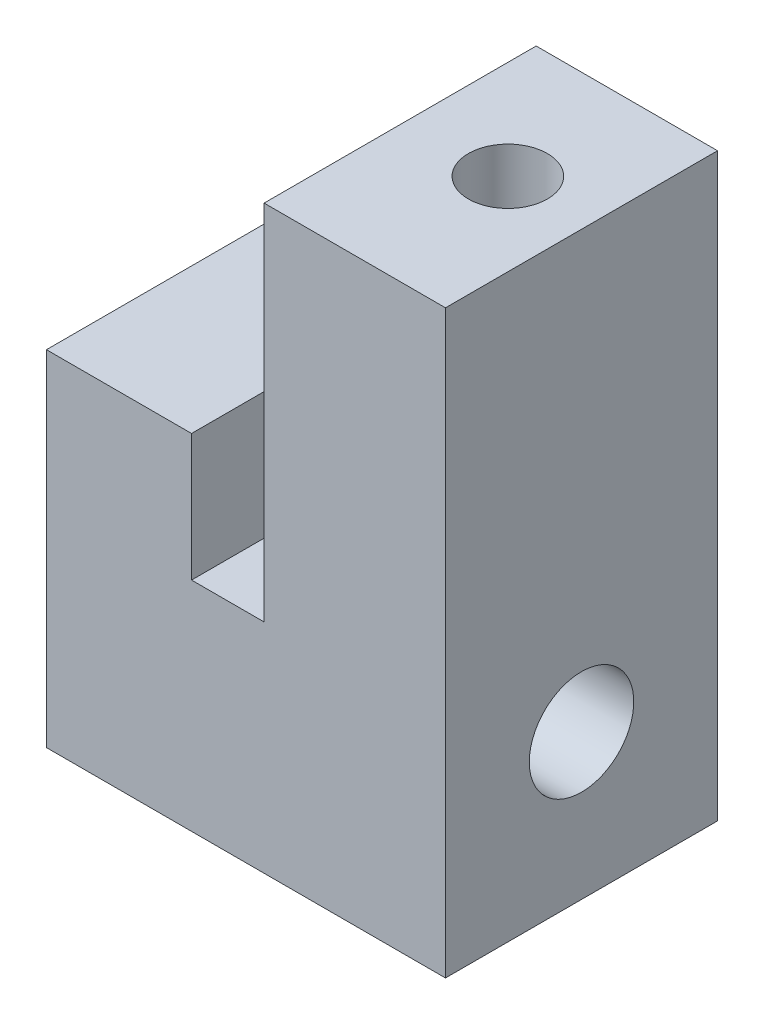
SolidWorks part; units mm, degrees
ref_plane "Front Plane" through (0, 0, 0) normal (0, 0, 1) x (1, 0, 0)
ref_plane "Top Plane" through (0, 0, 0) normal (0, 1, 0) x (1, 0, 0)
ref_plane "Right Plane" through (0, 0, 0) normal (1, 0, 0) x (0, 0, -1)
sketch "Sketch1" plane through (0, 0, 0) normal (0, 1, 0) x (1, 0, 0)
  line L1 (0, 0) -> (17.4625, 0)
  line L2 (0, 0) -> (0, 11.9062)
  line L3 (0, 11.9062) -> (17.4625, 11.9062)
  line L4 (17.4625, 0) -> (17.4625, 11.9062)
extrude "Boss-Extrude1" add sketch "Sketch1" along normal blind 25.4
sketch "Sketch2" plane through (0, 0, 0) normal (0, 0, 1) x (1, 0, 0)
  line L0 (6.35, 15.0812) -> (6.35, 9.525)
  line L5 (0, 25.4) -> (17.4625, 25.4)
  line L6 (6.35, 9.525) -> (9.525, 9.525)
  line L7 (6.35, 15.0812) -> (9.525, 15.0812)
  line L8 (0, 25.4) -> (0, 0)
  line L9 (6.35, 15.0812) -> (6.35, 9.525)
  line L10 (0, 25.4) -> (17.4625, 25.4) construction
  line L11 (0, 0) -> (17.4625, 0)
  line L12 (6.35, 9.525) -> (9.525, 9.525)
  line L13 (9.525, 15.0812) -> (9.525, 9.525)
  line L14 (9.525, 15.0812) -> (0, 15.0812)
  line L15 (9.525, 15.0812) -> (9.525, 9.525)
  line L16 (9.525, 9.525) -> (6.35, 9.525)
  line L17 (6.35, 15.0812) -> (6.35, 9.525)
  line L18 (9.525, 15.0812) -> (9.525, 25.4)
  line L19 (17.4625, 25.4) -> (17.4625, 0)
  line L20 (0, 25.4) -> (9.525, 25.4)
  line L21 (0, 25.4) -> (0, 15.0812)
  line L22 (0, 15.0812) -> (9.525, 15.0812)
  line L23 (9.525, 25.4) -> (9.525, 15.0812)
  line L25 (6.35, 9.525) -> (6.35, 0)
  line L26 (6.35, 0) -> (17.4625, 0)
  line L27 (17.4625, 9.525) -> (17.4625, 0)
  line L29 (17.4625, 9.525) -> (17.4625, 25.4)
  line L30 (17.4625, 25.4) -> (9.525, 25.4)
  line L31 (9.525, 9.525) -> (9.525, 25.4)
  line M4 (0, 25.4) -> (0, 0)
extrude "Cut-Extrude1" cut sketch "Sketch2" against normal blind 25.4 contours L7 L18 L5 L14 M4 | L13 L7 L0 L6
sketch "Sketch4" plane through (0, 0, 0) normal (-1, 0, 0) x (0, 0, 1)
  line L0 (-5.9531, 0) -> (-5.9531, 4.064)
  line L1 (-11.9062, 0) -> (0, 0) construction
  line L2 (-5.9531, 4.064) -> (-5.9531, 6.35)
  circle A0 centre (-5.9531, 6.35) radius 2.286
extrude "Cut-Extrude2" cut sketch "Sketch4" against normal blind 25.4
sketch "Sketch5" plane through (0, 25.4, 0) normal (0, 1, 0) x (1, 0, 0)
  line L0 (17.4625, 6.35) -> (15.494, 6.35)
  line L1 (17.4625, 0) -> (17.4625, 11.9062) construction
  line L2 (15.494, 6.35) -> (13.843, 6.35)
  circle A0 centre (13.843, 6.35) radius 1.651
hole_wizard "#8-32 Tapped Hole1" positions "Sketch7" profile "Sketch6" tap size "#8-32" standard "ANSI Inch"
sketch "Sketch7" plane through (0, 25.4, 0) normal (0, 1, 0) x (1, 0, 0)
  point P0 (13.843, 6.35)
sketch "Sketch6" plane through (13.843, 25.4, -6.35) normal (1, 0, 0) x (0, 0, 1)
  line L0 (0, 0) -> (0, 12.1503)
  line L1 (0, 12.1503) -> (1.7272, 11.1125)
  line L2 (1.7272, 11.1125) -> (1.7272, 0)
  line L5 (1.7272, 0) -> (0, 0)
  line L10 (0, 12.1503) -> (-1.7272, 11.1125) construction
  line L11 (0, -6.35) -> (0, 107.95) construction
  dimension "Tap Drill Dia." = 3.4544
  dimension "Tap Drill Depth" = 11.1125
  dimension "Drill Angle" = 118
cosmetic thread "Hole Thread2"
